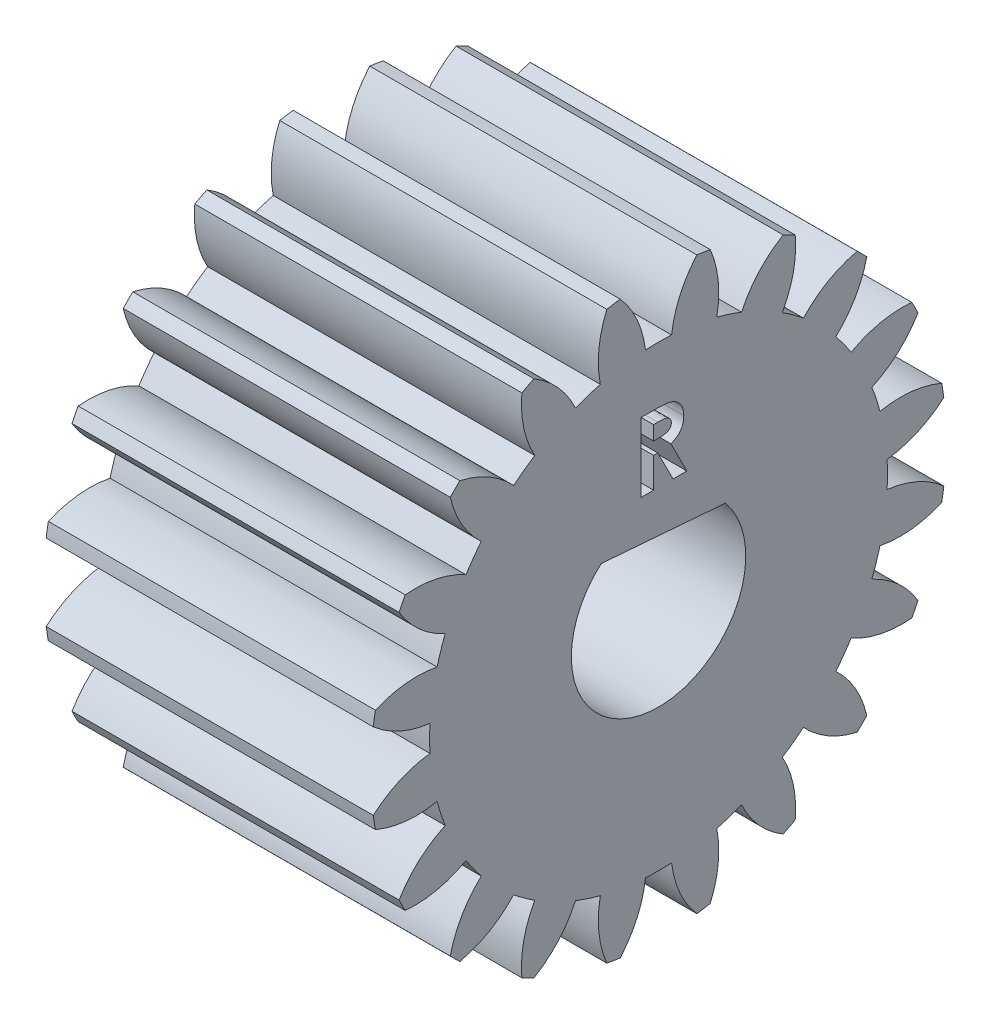
SolidWorks part; units mm, degrees
ref_plane "Plane1" through (0, 0, 0) normal (0, 0, 1) x (1, 0, 0)
ref_plane "Plane2" through (0, 0, 0) normal (0, 1, 0) x (1, 0, 0)
ref_plane "Plane3" through (0, 0, 0) normal (1, 0, 0) x (0, 0, -1)
sketch "HoldingSke" plane through (0, 0, 0) normal (0, 1, 0) x (1, 0, 0)
  line L0 (0, 0) -> (0.7831, -0.285)
  line L1 (-15, 0) -> (100, 0) construction
  line L2 (0, 0) -> (-2.1039, 2.3779)
  line L3 (0, 0) -> (-11.863, 4.5341)
  line L4 (0, 0) -> (8.1152, 2.9537)
  line L5 (0, 0) -> (-46.8476, -17.4728)
  line L6 (0, 0) -> (-12.4344, -8.3896)
  line L7 (-2.1039, 2.3779) -> (8.6586, 51.2059)
  line L8 (-76.2, 54.61) -> (-74.8, 54.61)
  line L9 (-71.009, 38.7566) -> (-53.1078, 45.2721)
  line L10 (-76.2, 71.12) -> (104.1128, 71.12)
  line L11 (0, 0) -> (-15, 0)
  line L12 (-76.2, 101.6) -> (-76.155, 101.6)
  line L13 (24.9733, 27.94) -> (52.9518, 28.4284)
  line L14 (24.9733, 27.94) -> (24.9743, 27.94)
  line L15 (24.9733, 27.94) -> (100.4006, 29.5858)
  line L16 (-63.627, -1.2) -> (-12.827, -1.2)
  circle A0 centre (0, 0) radius 4
  circle A1 centre (0, 0) radius 10.499
  circle A2 centre (0, 0) radius 37.5
  circle A3 centre (0, 0) radius 4
  dimension "MHD" = 20.998
  dimension "Hub_dia" = 75
  dimension "Bore" = 8
  dimension "MBD" = 8
  dimension "Num_teeth" = 20
  dimension "Pitch" = 0.8333
  dimension "Overall_len" = 50
  dimension "Show_teeth" = 20
  dimension "Thickness" = 15
  dimension "OAL" = 50.0001
  dimension "T_dim" = 1.4
  dimension "Ap" = 20
  dimension "H" = 19.05
  dimension "Pitch_radius" = 180.3128
  dimension "Width" = 15
  dimension "Backlash" = 0.045
  dimension "Addendum_fac" = 1
  dimension "Dedendum_fac" = 1.25
  dimension "Clearance_fac" = 0.25
  dimension "Dedendum_add" = 0.001
  dimension "Module" = 1.2
sketch "BasProSke" plane through (0, 0, 0) normal (0, 1, 0) x (1, 0, 0)
  line L0 (-10, 0) -> (60, 0) construction
  line L1 (0, 0) -> (0, 13.2)
  line L2 (0, 0) -> (15, 0)
  line L3 (15, 0) -> (15, 13.2)
  line L4 (15, 13.2) -> (0, 13.2)
  dimension "Thickness" = 15
  dimension "Diameter" = 26.4
revolve "Base-Revolve" add sketch "BasProSke" angle 360 about L0
sketch "TooCutSke" plane through (0, 0, 0) normal (1, 0, 0) x (0, 0, -1)
  line L1 (0, 0) -> (0, 107) construction
  line L2 (0, 0) -> (-1.0202, 11.9566) construction
  line L3 (0, 0) -> (-3.7447, 23.6432) construction
  line L4 (-1.0202, 11.9566) -> (-1.8724, 11.8216) construction
  arc A0 (0.599, 10.4819) -> (-0.599, 10.4819) centre (0, 0) ccw
  arc A1 (1.777, 13.1055) -> (-1.777, 13.1055) centre (0, 0) ccw
  circle A2 centre (0, 0) radius 12 construction
  circle A3 centre (0, 0) radius 11.2763 construction
  arc A4 (-0.599, 10.4819) -> (-1.777, 13.1055) centre (-5.3658, 9.9179) ccw
  arc A5 (1.777, 13.1055) -> (0.599, 10.4819) centre (5.3658, 9.9179) ccw
  dimension "Root_dia" = 20.998
  dimension "Overcut_dia" = 26.4508
  dimension "Pitch_dia" = 24
  dimension "Base_dia" = 22.5526
  dimension "Flank_rad" = 4.8
  dimension "Half_ang" = 9
  dimension "Half_CT" = 0.8628
extrude "ToothCut" cut sketch "TooCutSke" along normal through all
fillet "Breaks" [suppressed] radius 0.024
fillet "RootFillets" [suppressed] radius 0.301
pattern_circular "TeethCuts" count 20 every 18 about axis through (-10, 0, 0) along (1, 0, 0) of "ToothCut", "RootFillets", "Breaks"
sketch "HubNeaOneSke" plane through (0, 0, 0) normal (-1, 0, 0) x (0, 0, 1)
  circle A0 centre (0, 0) radius 10.499
  dimension "Diameter" = 20.998
extrude "HubNearOne" [suppressed] add sketch "HubNeaOneSke" along normal blind 35.0001
sketch "HubNeaBotSke" plane through (0, 0, 0) normal (-1, 0, 0) x (0, 0, 1)
  circle A0 centre (0, 0) radius 10.499
  dimension "Diameter" = 20.998
extrude "HubNearBoth" [suppressed] add sketch "HubNeaBotSke" along normal blind 17.5
ref_plane "FarPln" through (15, 0, 0) normal (1, 0, 0) x (0, 0, -1)
sketch "HubFarSke" plane through (15, 0, 0) normal (1, 0, 0) x (0, 0, -1)
  circle A0 centre (0, 0) radius 10.499
  dimension "Diameter" = 20.998
extrude "HubFar" [suppressed] add sketch "HubFarSke" along normal blind 17.5
sketch "BorSke" plane through (0, 0, 0) normal (1, 0, 0) x (0, 0, -1)
  circle A0 centre (0, 0) radius 4
  dimension "Diameter" = 8
extrude "Bore" cut sketch "BorSke" along normal mid plane 100.0001
sketch "KeySke" plane through (0, 0, 0) normal (1, 0, 0) x (0, 0, -1)
  line L0 (-1.5, 0) -> (-1.5, 5.4)
  line L1 (-1.5, 5.4) -> (1.5, 5.4)
  line L2 (1.5, 5.4) -> (1.5, 0)
  line L3 (0, 0) -> (0, 34) construction
  line L4 (-1.5, 0) -> (1.5, 0)
  dimension "Offset" = 5.4
  dimension "Width" = 3
extrude "Keyway" [suppressed] cut sketch "KeySke" along normal mid plane 100.0001
pattern_circular "Keyway2" [suppressed] count 2 every 90 about axis through (-10, 0, 0) along (1, 0, 0)
sketch "Sketch1" plane through (0, 0, 0) normal (-1, 0, 0) x (0, 0, 1)
  line L0 (0, 0) -> (0, 8) construction
  line L1 (0, 0) -> (-0.2197, 2.7914) construction
  line L2 (-0.2197, 2.7914) -> (-0.3138, 3.9877) construction
  line L3 (2.6281, 3.0155) -> (-3.0675, 2.5672)
  circle A0 centre (0, 0) radius 4 construction
  circle A1 centre (0, 0) radius 8 construction
  circle A2 centre (0, 0) radius 4 construction
  arc A3 (2.6281, 3.0155) -> (-3.0675, 2.5672) centre (0, 0) ccw
  point P12 (-0.2197, 2.7914)
  dimension "D1" = 16
  dimension "D2" = 1.2
  dimension "D3" = 4.5
extrude "Boss-Extrude1" add sketch "Sketch1" against normal up to surface (15 mm away) up to face at (15, 0, 4)
sketch "Sketch2" plane through (0, 0, 0) normal (-1, 0, 0) x (0, 0, 1)
  circle A0 centre (0, 0) radius 6
  circle A1 centre (0, 0) radius 7.2
  dimension "D1" = 12
  dimension "D2" = 14.4
extrude "Cut-Extrude1" cut sketch "Sketch2" against normal blind 0.5
sketch "Sketch3" plane through (15, 0, 0) normal (1, 0, 0) x (0, 0, -1)
  text T0 "R" font "Century Gothic" height in points 12
extrude "Cut-Extrude2" cut sketch "Sketch3" against normal blind 2
equation "' \"Module@HoldingSke\" = 6.35"
equation "' \"Num_teeth@HoldingSke\" = 12"
equation "' \"Ap@HoldingSke\" =  20"
equation "' \"Ap@HoldingSke\" = 20"
equation "' \"Width@HoldingSke\" = 0.5 * 25.4"
equation "' \"Hub_dia@HoldingSke\"= 1 * 25.4"
equation "' \"Hub_dia@HoldingSke\" = 1 * 25.4"
equation "' \"Overall_len@HoldingSke\" = 1.0 * 25.4"
equation "' \"Bore@HoldingSke\" = 0.75 * 25.4"
equation "' \"T_dim@HoldingSke\" = 0.1 * 25.4"
equation "' \"Width@KeySke\" = 0.25 * 25.4"
equation "' \"Show_teeth@HoldingSke\" = 13"
equation "' \"Backlash@HoldingSke\" = 0.009 * 25.4"
equation "' \"Addendum_fac@HoldingSke\" = 1.0"
equation "' \"Dedendum_fac@HoldingSke\" = 1.25"
equation "' \"Dedendum_add@HoldingSke\" = 0.00005 * 25.4"
equation "' \"Clearance_fac@HoldingSke\" = 0.25"
equation "\"Pitch@HoldingSke\" = 1 / \"Module@HoldingSke\""
equation "\"Overcut_dia@TooCutSke\" = (\"Num_teeth@HoldingSke\" + 2 * \"Addendum_fac@HoldingSke\") / \"Pitch@HoldingSke\" + 0.002 * 25.4"
equation "\"Pitch_dia@TooCutSke\" = \"Num_teeth@HoldingSke\" / \"Pitch@HoldingSke\""
equation "\"Base_dia@TooCutSke\" = \"Num_teeth@HoldingSke\" / \"Pitch@HoldingSke\" * cos((\"Ap@HoldingSke\"  * 3.14159265 / 180))"
equation "\"Root_dia@TooCutSke\" = (\"Num_teeth@HoldingSke\" + 2) / \"Pitch@HoldingSke\" - 2 * (\"Addendum_fac@HoldingSke\" + \"Dedendum_fac@HoldingSke\") / \"Pitch@HoldingSke\" - \"Dedendum_add@HoldingSke\" * 2"
equation "\"Half_ang@TooCutSke\" = 180 / \"Num_teeth@HoldingSke\""
equation "\"Half_CT@TooCutSke\" = \"Num_teeth@HoldingSke\" / \"Pitch@HoldingSke\" * sin((3.14159265 / 2 / \"Num_teeth@HoldingSke\")) / 2 - 7 * \"Backlash@HoldingSke\" / 4"
equation "\"Flank_rad@TooCutSke\" = \"Num_teeth@HoldingSke\" / \"Pitch@HoldingSke\" / 5"
equation "\"Radius@RootFillets\" = \"Clearance_fac@HoldingSke\" / \"Pitch@HoldingSke\" + \"Dedendum_add@HoldingSke\""
equation "\"Break_rad@Breaks\" = 0.02 / \"Pitch@HoldingSke\""
equation "\"Thickness@HoldingSke\" = \"Width@HoldingSke\""
equation "\"OAL@HoldingSke\" = \"Thickness@HoldingSke\""
equation "\"MHD@HoldingSke\" = (\"Num_teeth@HoldingSke\" + 2) / \"Pitch@HoldingSke\" - 2 * (\"Addendum_fac@HoldingSke\" + \"Dedendum_fac@HoldingSke\")  / \"Pitch@HoldingSke\" - \"Dedendum_add@HoldingSke\" * 2"
equation "\"MBD@HoldingSke\" = (\"Num_teeth@HoldingSke\" + 2) / \"Pitch@HoldingSke\" - 2 * (\"Addendum_fac@HoldingSke\" + \"Dedendum_fac@HoldingSke\")  / \"Pitch@HoldingSke\" - \"Dedendum_add@HoldingSke\" * 2 - 0.002 * 25.4"
equation "\"MHD@HoldingSke\" = ((sgn( \"MHD@HoldingSke\" - \"Hub_dia@HoldingSke\" )-1)*( \"MHD@HoldingSke\" - \"Hub_dia@HoldingSke\" ))/-2+ \"Hub_dia@HoldingSke\""
equation "\"MBD@HoldingSke\" = ((sgn( \"MBD@HoldingSke\" - \"Bore@HoldingSke\" )-1)*( \"MBD@HoldingSke\" - \"Bore@HoldingSke\" ))/-2+ \"Bore@HoldingSke\""
equation "\"OAL@HoldingSke\" = ((sgn( \"OAL@HoldingSke\" - \"Overall_len@HoldingSke\" )+1)*( \"OAL@HoldingSke\" - \"Overall_len@HoldingSke\" ))/2 + \"Overall_len@HoldingSke\" + 0.000002 * 25.4"
equation "\"Num_teeth@TeethCuts\" = int( \"Show_teeth@HoldingSke\" ) + 1"
equation "\"Num_teeth@TeethCuts\" = ((sgn( \"Num_teeth@TeethCuts\" - \"Num_teeth@HoldingSke\" )-1)*( \"Num_teeth@TeethCuts\" - \"Num_teeth@HoldingSke\" ))/-2+ \"Num_teeth@HoldingSke\""
equation "\"Num_teeth@TeethCuts\" = ((sgn( \"Num_teeth@TeethCuts\" - 2.0)+1)*( \"Num_teeth@TeethCuts\" - 2.0))/2 +2.0"
equation "\"Angle@TeethCuts\" = 360.0 / \"Num_teeth@HoldingSke\""
equation "\"Diameter@BasProSke\" = (\"Num_teeth@HoldingSke\" + 2 * \"Addendum_fac@HoldingSke\") / \"Pitch@HoldingSke\""
equation "\"Thickness@BasProSke\"  = \"Thickness@HoldingSke\""
equation "' \"Fillet_rad@BasProSke\" =  \"Thickness@HoldingSke\" * 0.05"
equation "' \"Fillet_rad@BasProSke\" = \"Thickness@HoldingSke\" * 0.05"
equation "\"MHD@HoldingSke\" = ((sgn( \"MHD@HoldingSke\" - \"Root_dia@TooCutSke\" )-1)*( \"MHD@HoldingSke\" - \"Root_dia@TooCutSke\" ))/-2+ \"Root_dia@TooCutSke\""
equation "\"Diameter@HubNeaOneSke\" = \"MHD@HoldingSke\""
equation "\"Length@HubNearOne\" = \"OAL@HoldingSke\" - \"Thickness@BasProSke\""
equation "\"Diameter@HubNeaBotSke\" = \"MHD@HoldingSke\""
equation "\"Length@HubNearBoth\" = ( \"OAL@HoldingSke\" - \"Thickness@BasProSke\" ) / 2.0"
equation "\"Thickness@FarPln\" = \"Thickness@BasProSke\""
equation "\"Diameter@HubFarSke\" = \"MHD@HoldingSke\""
equation "\"Length@HubFar\" = ( \"OAL@HoldingSke\" - \"Thickness@BasProSke\" ) / 2.0"
equation "\"Diameter@BorSke\" = \"MBD@HoldingSke\""
equation "\"D1@Bore\" = \"OAL@HoldingSke\" * 2.0"
equation "\"D1@Keyway\" = \"OAL@HoldingSke\" * 2.0"
equation "\"Offset@KeySke\" = \"T_dim@HoldingSke\" + \"MBD@HoldingSke\" / 2.0"
